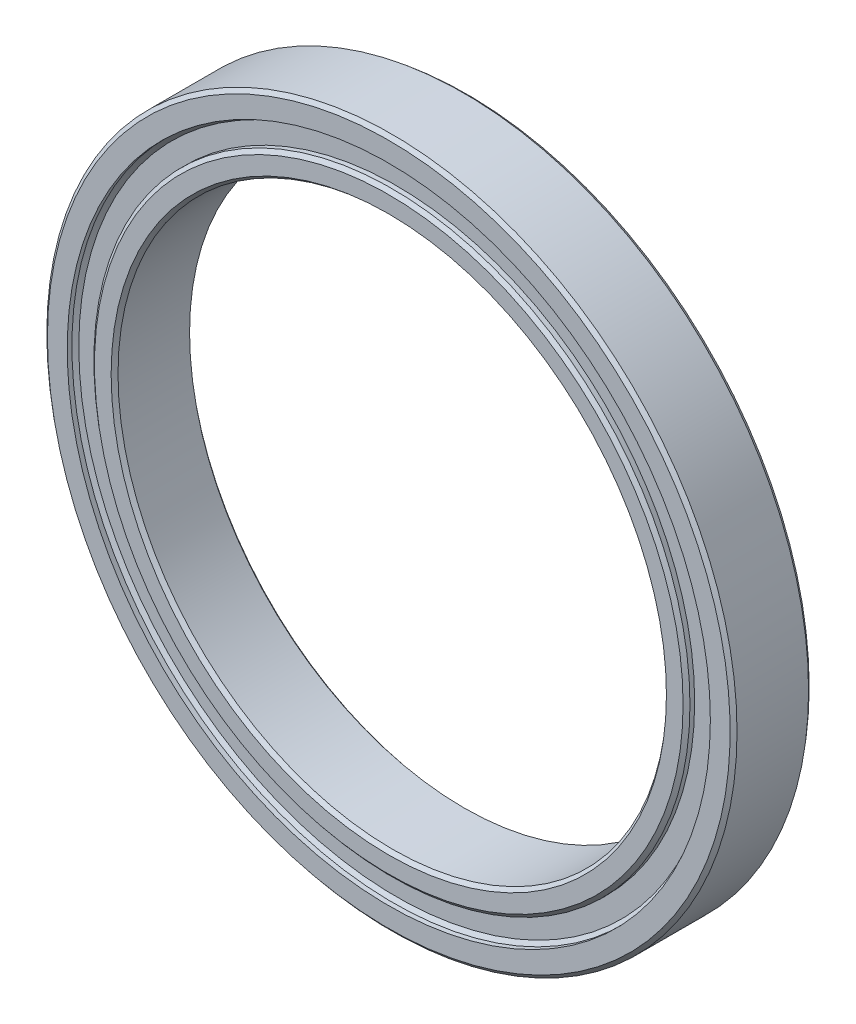
SolidWorks part; units mm, degrees
material "普通碳钢"
ref_plane "前视基准面" through (0, 0, 0) normal (0, 0, 1) x (1, 0, 0)
ref_plane "上视基准面" through (0, 0, 0) normal (0, 1, 0) x (1, 0, 0)
ref_plane "右视基准面" through (0, 0, 0) normal (1, 0, 0) x (0, 0, -1)
sketch "草图1" plane through (0, 0, 0) normal (0, 0, 1) x (1, 0, 0)
  circle A0 centre (0, 0) radius 22
  circle A1 centre (0, 0) radius 17.5
  dimension "D1" = 44
  dimension "D2" = 35
extrude "凸台-拉伸1" add sketch "草图1" along normal blind 5
sketch "草图2" plane through (0, 0, 5) normal (0, 0, 1) x (1, 0, 0)
  circle A0 centre (0, 0) radius 19
  circle A1 centre (0, 0) radius 20.5
  dimension "D1" = 38
  dimension "D2" = 41
extrude "切除-拉伸1" cut sketch "草图2" against normal blind 0.5
chamfer "倒角1" distance 0.2 angle 50 4 edges at (19, 0, 5) (20.5, 0, 4.5) (22, 0, 5) (17.5, 0, 5)
ref_plane "基准面4" through (0, 0, 2.5) normal (0, 0, 1) x (1, 0, 0)
mirror "镜向1" about plane through (0, 0, 2.5) normal (0, 0, 1) of "切除-拉伸1"
chamfer "倒角2" distance 0.2 angle 50 4 edges at (17.5, 0, 0) (19, 0, 0) (20.5, 0, 0) (22, 0, 0)
